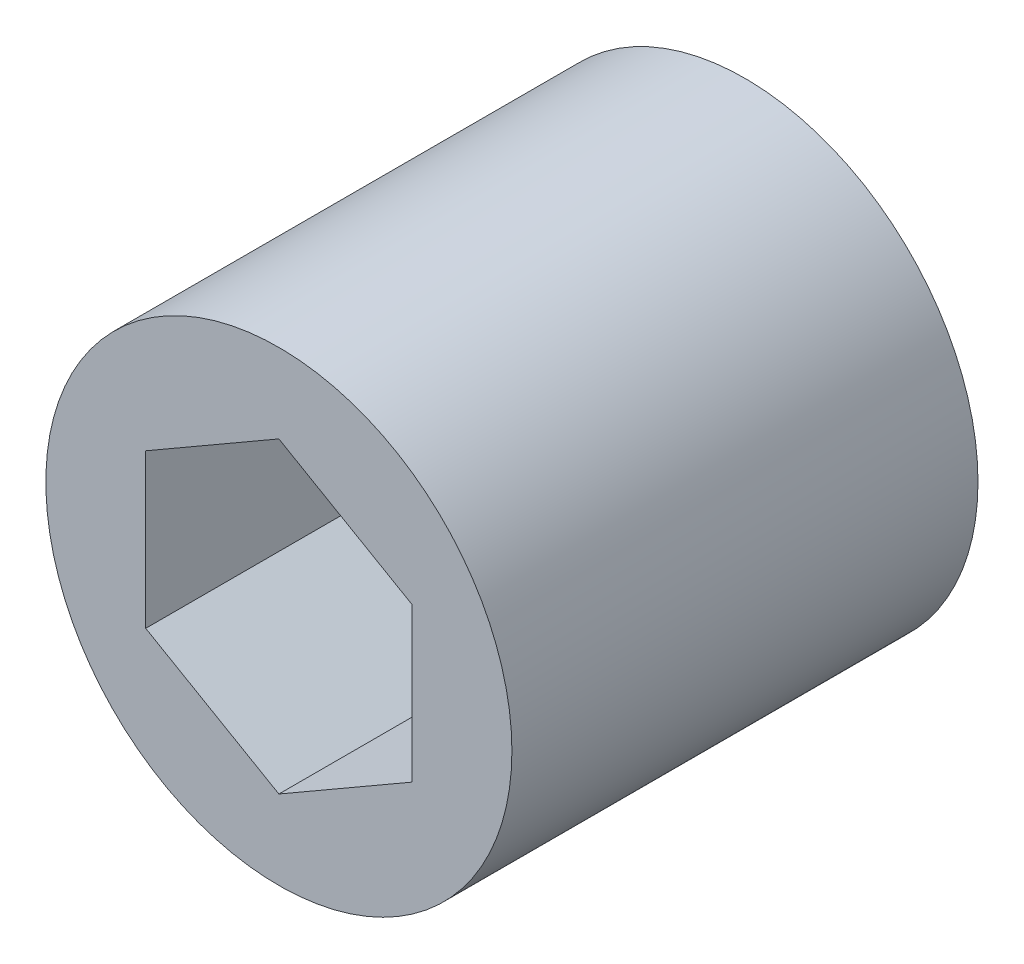
SolidWorks part; units mm, degrees
material "Nylon 101"
ref_plane "Front Plane" through (0, 0, 0) normal (0, 0, 1) x (1, 0, 0)
ref_plane "Top Plane" through (0, 0, 0) normal (0, 1, 0) x (1, 0, 0)
ref_plane "Right Plane" through (0, 0, 0) normal (1, 0, 0) x (0, 0, -1)
sketch "Sketch1" plane through (0, 0, 0) normal (0, 0, 1) x (1, 0, 0)
  line L1 (0, 7.3323) -> (-6.35, 3.6662)
  line L2 (-6.35, 3.6662) -> (-6.35, -3.6662)
  line L3 (-6.35, -3.6662) -> (0, -7.3323)
  line L4 (0, -7.3323) -> (6.35, -3.6662)
  line L5 (6.35, -3.6662) -> (6.35, 3.6662)
  line L6 (6.35, 3.6662) -> (0, 7.3323)
  circle A0 centre (0, 0) radius 11.1125
  circle A1 centre (0, 0) radius 6.35 construction
  dimension "D1" = 12.7
  dimension "D2" = 22.225
extrude "Boss-Extrude1" add sketch "Sketch1" along normal blind 22.225
